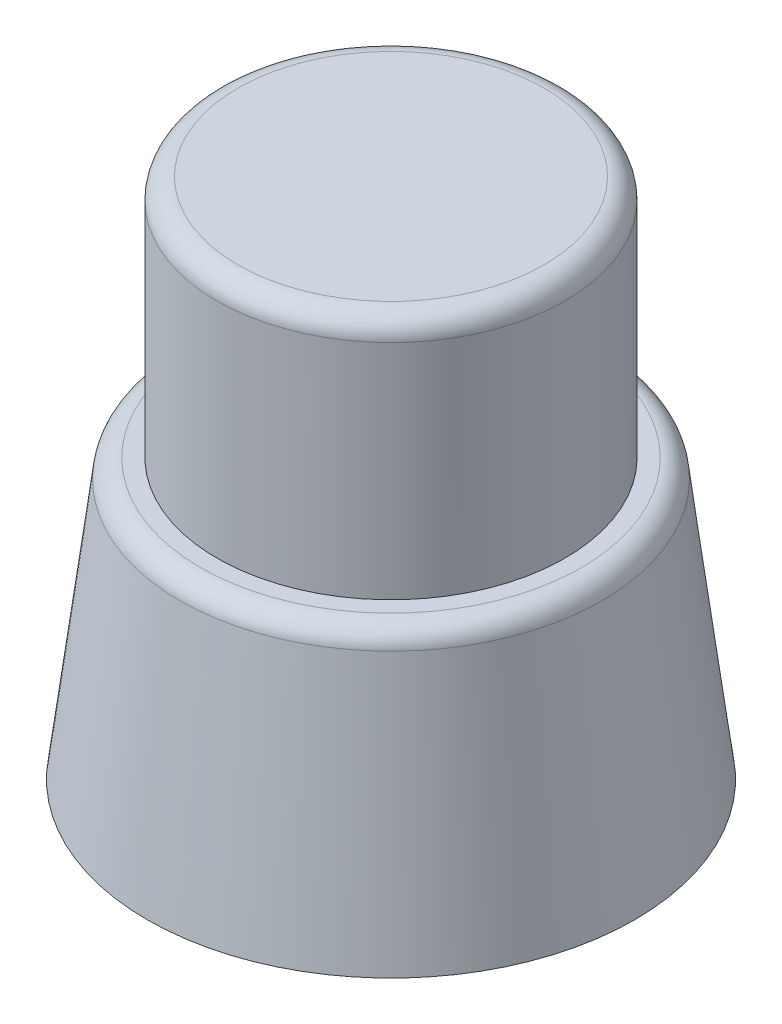
SolidWorks part; units mm, degrees
ref_plane "Front Plane" through (0, 0, 0) normal (0, 0, 1) x (1, 0, 0)
ref_plane "Top Plane" through (0, 0, 0) normal (0, 1, 0) x (1, 0, 0)
ref_plane "Right Plane" through (0, 0, 0) normal (1, 0, 0) x (0, 0, -1)
sketch "Sketch1" plane through (0, 0, 0) normal (0, 0, 1) x (1, 0, 0)
  line L0 (0, 0) -> (0, 75) construction
  line L1 (0, 75) -> (25, 75)
  line L2 (25, 75) -> (25, 40)
  line L3 (25, 40) -> (30, 40)
  line L4 (30, 40) -> (35, 0)
  line L5 (35, 0) -> (0, 0)
  line L6 (0, 0) -> (0, 75)
  dimension "D1" = 75
  dimension "D2" = 25
  dimension "D3" = 35
  dimension "D4" = 40
  dimension "D5" = 5
revolve "Revolve1" add sketch "Sketch1" angle 360 about L0
fillet "Fillet1" radius 3 2 edges at (0, 40, -30) (0, 75, -25)
shell "Shell1" thickness 2
